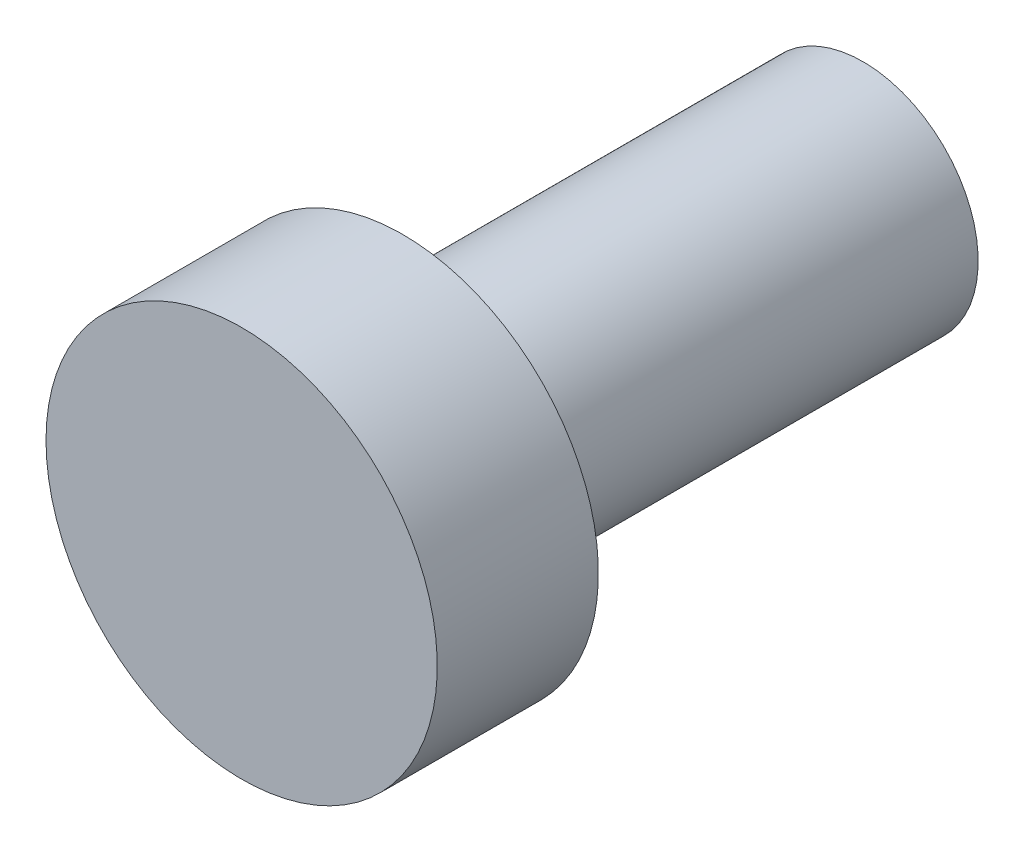
SolidWorks part; units mm, degrees
material "1.1191 (C45E)"
ref_plane "Front Plane" through (0, 0, 0) normal (0, 0, 1) x (1, 0, 0)
ref_plane "Top Plane" through (0, 0, 0) normal (0, 1, 0) x (1, 0, 0)
ref_plane "Right Plane" through (0, 0, 0) normal (1, 0, 0) x (0, 0, -1)
sketch "Sketch1" plane through (0, 0, 0) normal (0, 1, 0) x (1, 0, 0)
  line L0 (0, -3.5) -> (4.25, -3.5)
  line L1 (4.25, -3.5) -> (4.25, 0)
  line L2 (4.25, 0) -> (2.5, 0)
  line L3 (2.5, 0) -> (2.5, 10)
  line L4 (2.5, 10) -> (0, 10)
  line L5 (0, 10) -> (0, -3.5) construction
  line L6 (0, -3.5) -> (0, 10)
revolve "REV_DIN7984_M5x10_8.8" add sketch "Sketch1" angle 360 about L5
